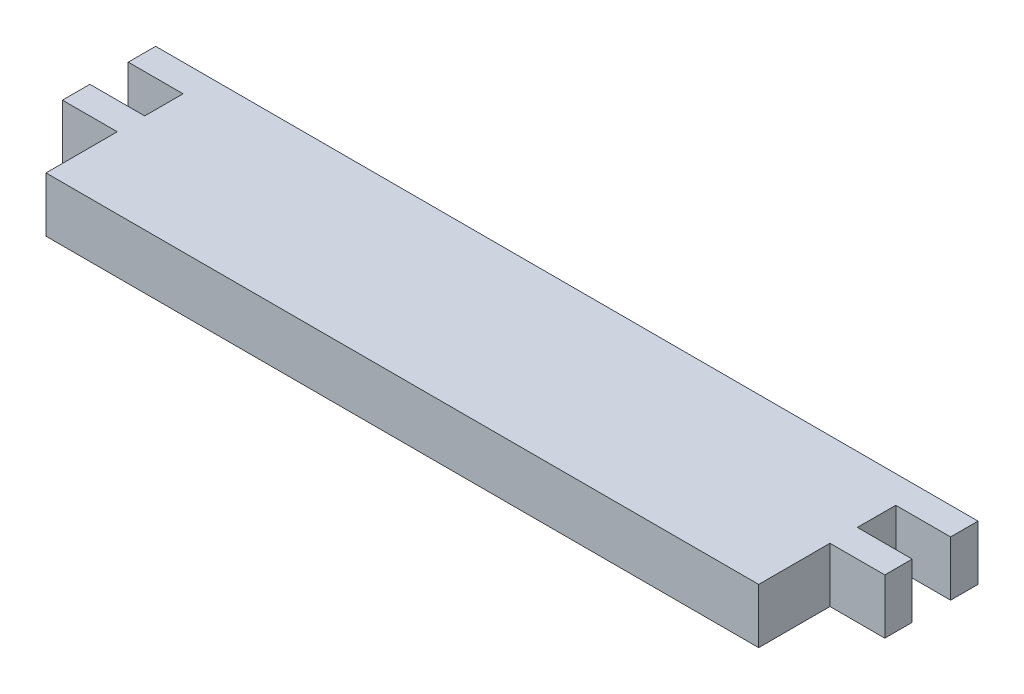
SolidWorks part; units mm, degrees
ref_plane "정면" through (0, 0, 0) normal (0, 0, 1) x (1, 0, 0)
ref_plane "윗면" through (0, 0, 0) normal (0, 1, 0) x (1, 0, 0)
ref_plane "우측면" through (0, 0, 0) normal (1, 0, 0) x (0, 0, -1)
sketch "스케치1" plane through (0, 0, 0) normal (0, 0, 1) x (1, 0, 0)
  line L1 (-65, 5) -> (65, 5)
  line L2 (-65, 5) -> (-65, -5)
  line L3 (-65, -5) -> (65, -5)
  line L4 (65, 5) -> (65, -5)
  line L5 (-65, 5) -> (65, -5) construction
  line L6 (-65, -5) -> (65, 5) construction
  point P0 (0, 0)
  dimension "D1" = 130
  dimension "D2" = 10
extrude "보스-돌출1" add sketch "스케치1" along normal blind 7
sketch "스케치2" plane through (0, 0, 0) normal (0, 0, -1) x (-1, 0, 0)
  line L1 (-75, 5) -> (75, 5)
  line L2 (-75, 5) -> (-75, -5)
  line L3 (-75, -5) -> (75, -5)
  line L4 (75, 5) -> (75, -5)
  line L5 (-75, 5) -> (75, -5) construction
  line L6 (-75, -5) -> (75, 5) construction
  point P0 (0, 0)
  dimension "D1" = 10
  dimension "D2" = 150
extrude "보스-돌출2" add sketch "스케치2" along normal blind 5
sketch "스케치5" plane through (0, 0, 7) normal (0, 0, 1) x (1, 0, 0)
  line L1 (-65, 5) -> (65, 5)
  line L2 (-65, 5) -> (-65, -5)
  line L3 (-65, -5) -> (65, -5)
  line L4 (65, 5) -> (65, -5)
extrude "보스-돌출4" add sketch "스케치5" along normal blind 18
sketch "스케치3" plane through (0, -5, 0) normal (0, 1, 0) x (1, 0, 0)
  line L1 (-59, -22) -> (-29, -22)
  line L2 (-59, -22) -> (-59, -4)
  line L3 (-59, -4) -> (-29, -4)
  line L4 (-29, -22) -> (-29, -4)
  line L5 (-65, -25) -> (-65, 0) construction
  line L6 (29, -22) -> (59, -22)
  line L7 (29, -22) -> (29, -4)
  line L8 (29, -4) -> (59, -4)
  line L9 (59, -22) -> (59, -4)
  line L10 (65, -25) -> (65, 0) construction
  line L11 (-75, 5) -> (75, 5) construction
  dimension "D1" = 30
  dimension "D2" = 30
  dimension "D3" = 6
  dimension "D4" = 6
  dimension "D5" = 18
  dimension "D6" = 18
  dimension "D7" = 9
  dimension "D8" = 9
extrude "컷-돌출1" cut sketch "스케치3" along normal blind 4
sketch "스케치6" plane through (-65, 0, 0) normal (-1, 0, 0) x (0, 0, 1)
  line L0 (25, 5) -> (0, 5) construction
  line L1 (7, 5) -> (12, 5)
  line L2 (7, 5) -> (7, -5)
  line L3 (7, -5) -> (12, -5)
  line L4 (12, 5) -> (12, -5)
  line L5 (25, -5) -> (0, -5) construction
  line L6 (0, 5) -> (0, -5) construction
  dimension "D1" = 7
  dimension "D2" = 5
extrude "보스-돌출5" add sketch "스케치6" along normal up to vertex (10 mm away) up to point (-75, -5, -5)
ref_plane "평면1" through (0, 0, 0) normal (-1, 0, 0) x (0, 0, 1)
mirror "대칭 복사1" about plane through (0, 0, 0) normal (-1, 0, 0) of "보스-돌출5"
